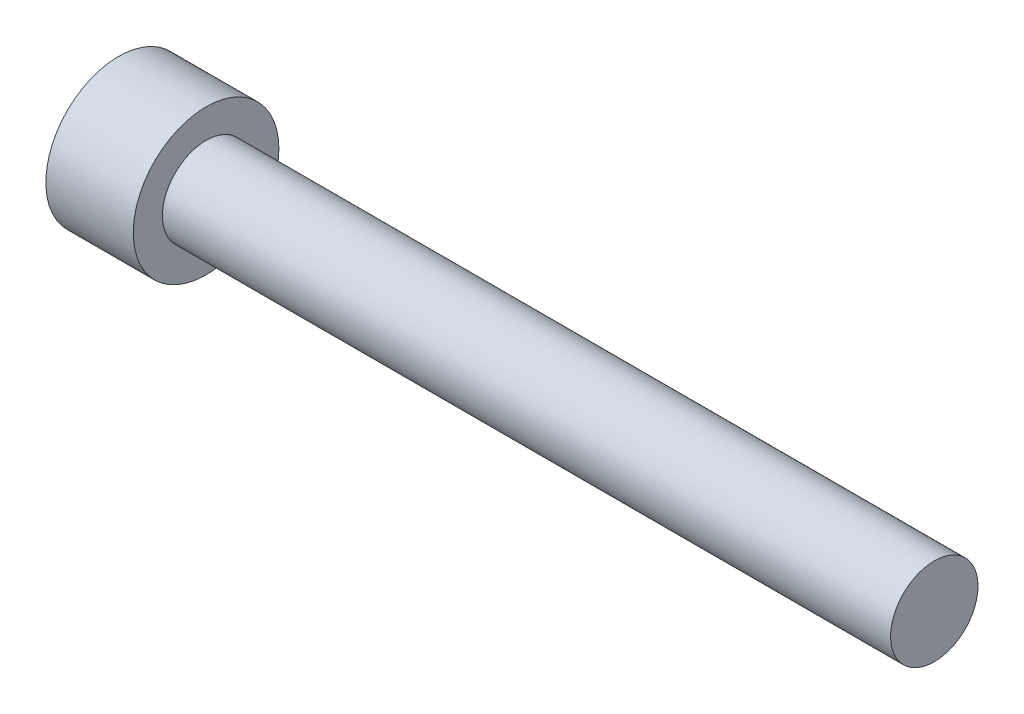
SolidWorks part; units mm, degrees
ref_plane "Front Plane" through (0, 0, 0) normal (0, 0, 1) x (1, 0, 0)
ref_plane "Top Plane" through (0, 0, 0) normal (0, 1, 0) x (1, 0, 0)
ref_plane "Right Plane" through (0, 0, 0) normal (1, 0, 0) x (0, 0, -1)
sketch "Sketch1" plane through (0, 0, 0) normal (0, 1, 0) x (1, 0, 0)
  line L0 (0, 0) -> (0, 2.5)
  line L1 (0, 2.5) -> (3, 2.5)
  line L2 (3, 2.5) -> (3, 1.5)
  line L3 (3, 1.5) -> (28, 1.5)
  line L4 (28, 1.5) -> (28, 0)
  line L5 (28, 0) -> (0, 0)
  dimension "D1" = 3
  dimension "D2" = 2.5
  dimension "D3" = 1.5
  dimension "D4" = 25
revolve "Revolve1" add sketch "Sketch1" angle 360 about L5
